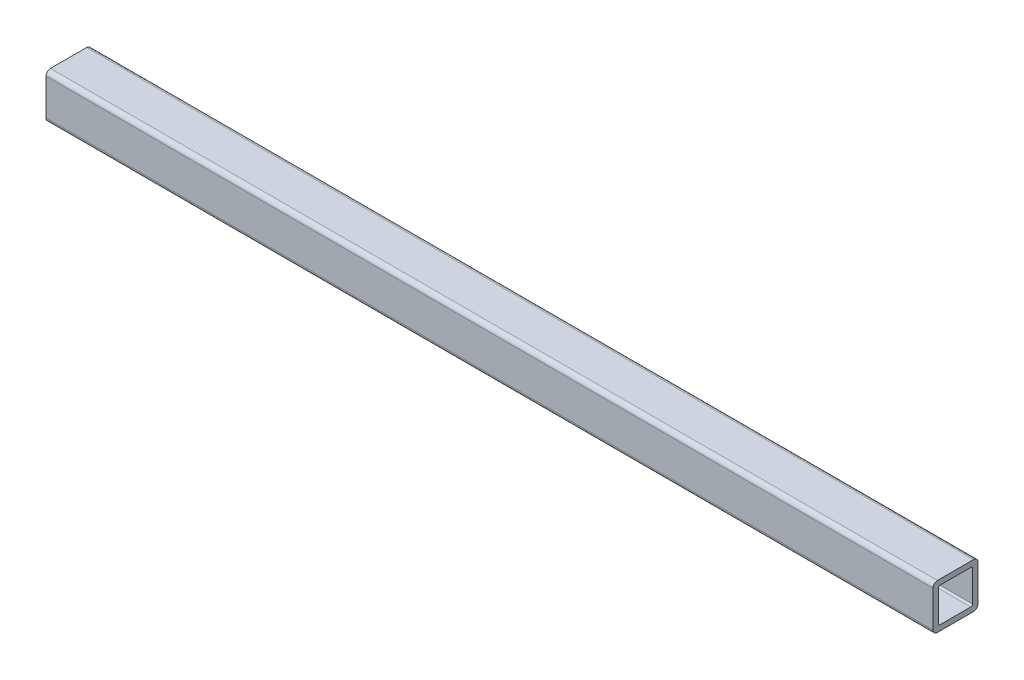
SolidWorks part; units mm, degrees
ref_plane "Front Plane" through (0, 0, 0) normal (0, 0, 1) x (1, 0, 0)
ref_plane "Top Plane" through (0, 0, 0) normal (0, 1, 0) x (1, 0, 0)
ref_plane "Right Plane" through (0, 0, 0) normal (1, 0, 0) x (0, 0, -1)
sketch "Sketch3" plane through (0, 0, 0) normal (1, 0, 0) x (0, 0, -1)
  line L1 (-12.7, 12.7) -> (12.7, 12.7)
  line L2 (-12.7, 12.7) -> (-12.7, -12.7)
  line L3 (-12.7, -12.7) -> (12.7, -12.7)
  line L4 (12.7, 12.7) -> (12.7, -12.7)
  line L5 (-12.7, 12.7) -> (12.7, -12.7) construction
  line L6 (-12.7, -12.7) -> (12.7, 12.7) construction
  line L7 (-9.652, -9.652) -> (9.652, -9.652)
  line L8 (-9.652, -9.652) -> (-9.652, 9.652)
  line L9 (-9.652, 9.652) -> (9.652, 9.652)
  line L10 (9.652, -9.652) -> (9.652, 9.652)
  line L11 (-9.652, -9.652) -> (9.652, 9.652) construction
  line L12 (-9.652, 9.652) -> (9.652, -9.652) construction
  point P0 (0, 0)
  point P6 (0, 0)
  dimension "D1" = 25.4
  dimension "D2" = 19.304
  dimension "D3" = 19.304
  dimension "D4" = 25.4
extrude "Boss-Extrude1" add sketch "Sketch3" against normal blind 500
fillet "Fillet1" radius 2.5 4 edges at (-250, -12.7, -12.7) (-250, -12.7, 12.7) (-250, 12.7, -12.7) (-250, 12.7, 12.7)
fillet "Fillet2" radius 1 4 edges at (-250, -9.652, -9.652) (-250, 9.652, -9.652) (-250, 9.652, 9.652) (-250, -9.652, 9.652)
